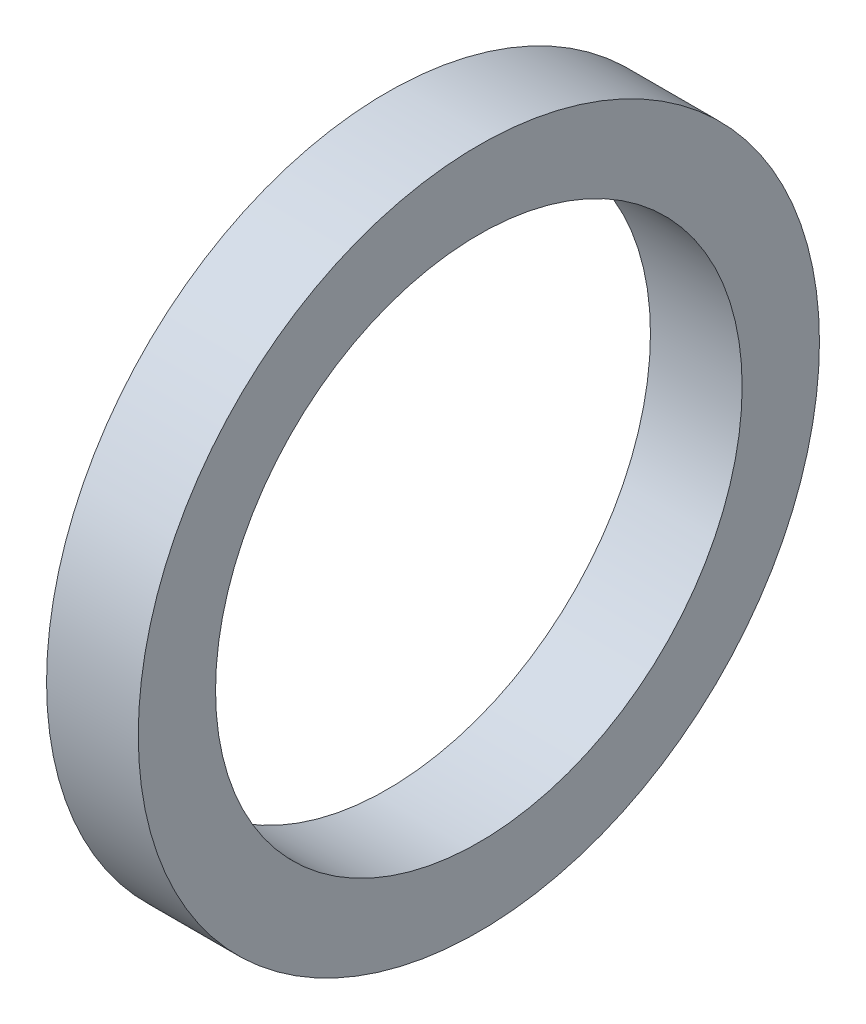
SolidWorks part; units mm, degrees
ref_plane "Front Plane" through (0, 0, 0) normal (0, 0, 1) x (1, 0, 0)
ref_plane "Top Plane" through (0, 0, 0) normal (0, 1, 0) x (1, 0, 0)
ref_plane "Right Plane" through (0, 0, 0) normal (1, 0, 0) x (0, 0, -1)
sketch "Sketch1" plane through (0, 0, 0) normal (1, 0, 0) x (0, 0, -1)
  circle A0 centre (0, 0) radius 26
  circle A1 centre (0, 0) radius 20.1
  dimension "D1" = 40.2
  dimension "D2" = 52
extrude "Boss-Extrude1" add sketch "Sketch1" along normal blind 7
